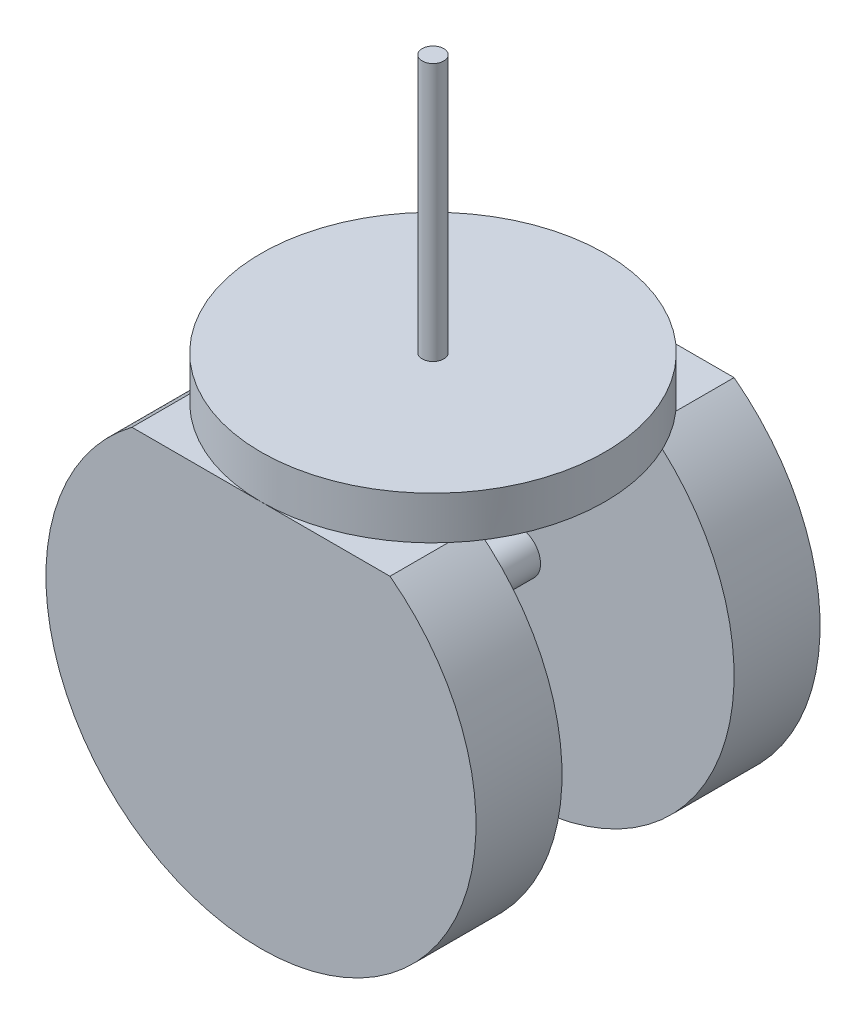
SolidWorks part; units mm, degrees
ref_plane "Front Plane" through (0, 0, 0) normal (0, 0, 1) x (1, 0, 0)
ref_plane "Top Plane" through (0, 0, 0) normal (0, 1, 0) x (1, 0, 0)
ref_plane "Right Plane" through (0, 0, 0) normal (1, 0, 0) x (0, 0, -1)
sketch "Sketch2" plane through (0, 0, 0) normal (0, 0, 1) x (1, 0, 0)
  circle A0 centre (0, 0) radius 63.5
  dimension "D1" = 127
extrude "Boss-Extrude1" add sketch "Sketch2" along normal blind 25.4
sketch "Sketch3" plane through (0, 0, 0) normal (0, 0, -1) x (-1, 0, 0)
  circle A0 centre (0, 0) radius 6.35
  dimension "D1" = 12.7
extrude "Boss-Extrude2" add sketch "Sketch3" along normal blind 50.8
sketch "Sketch4" plane through (0, 0, -50.8) normal (0, 0, -1) x (-1, 0, 0)
  circle A0 centre (0, 0) radius 63.5
  dimension "D1" = 127
extrude "Boss-Extrude3" add sketch "Sketch4" along normal blind 25.4
sketch "Sketch5" plane through (0, 0, 0) normal (0, 1, 0) x (1, 0, 0)
  line L1 (-63.5, -25.4) -> (63.5, -25.4)
  line L2 (-63.5, -25.4) -> (-63.5, 76.2)
  line L3 (-63.5, 76.2) -> (63.5, 76.2)
  line L4 (63.5, -25.4) -> (63.5, 76.2)
extrude "Cut-Extrude1" cut sketch "Sketch5" against normal blind 25.4 from offset 76.2
sketch "Sketch6" plane through (0, 50.8, 0) normal (0, 1, 0) x (1, 0, 0)
  line L0 (-38.1, -25.4) -> (38.1, -25.4) construction
  line L1 (38.1, 76.2) -> (-38.1, 76.2) construction
  circle A0 centre (0, 25.4) radius 50.8
  point P6 (0, 0)
extrude "Boss-Extrude4" add sketch "Sketch6" along normal blind 12.7
sketch "Sketch7" plane through (0, 63.5, 0) normal (0, 1, 0) x (1, 0, 0)
  circle A0 centre (0, 25.4) radius 3.175
  circle A1 centre (0, 25.4) radius 50.8 construction
  point P2 (0, 0)
  dimension "D1" = 6.35
extrude "Boss-Extrude5" add sketch "Sketch7" along normal blind 76.2
